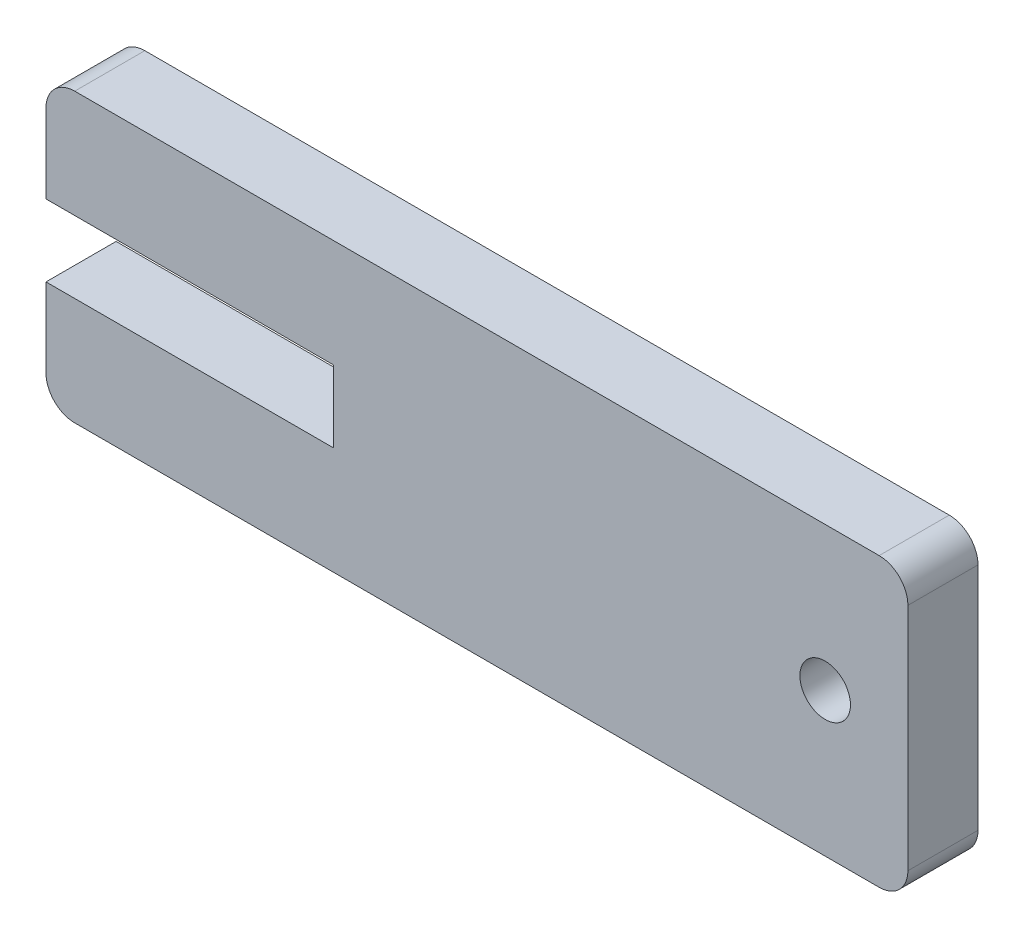
SolidWorks part; units mm, degrees
material "Corrugated Paper"
ref_plane "Front Plane" through (0, 0, 0) normal (0, 0, 1) x (1, 0, 0)
ref_plane "Top Plane" through (0, 0, 0) normal (0, 1, 0) x (1, 0, 0)
ref_plane "Right Plane" through (0, 0, 0) normal (1, 0, 0) x (0, 0, -1)
sketch "Sketch1" plane through (0, 0, 0) normal (0, 0, 1) x (1, 0, 0)
  line L0 (-12.7, 1.5875) -> (-12.7, 6.35)
  line L1 (-12.7, -1.5875) -> (0, -1.5875)
  line L3 (-12.7, 1.5875) -> (0, 1.5875)
  line L4 (0, -1.5875) -> (0, 1.5875)
  line L5 (-12.7, 6.35) -> (25.4, 6.35)
  line L6 (0, 0) -> (25.4, 0) construction
  line L7 (25.4, 6.35) -> (25.4, -6.35)
  line L8 (-12.7, -6.35) -> (25.4, -6.35)
  line L9 (-12.7, -1.5875) -> (-12.7, -6.35)
  dimension "D1" = 12.7
  dimension "D2" = 3.175
  dimension "D3" = 25.4
  dimension "D4" = 12.7
extrude "Boss-Extrude1" add sketch "Sketch1" along normal mid plane 3.0988
fillet "Fillet1" radius 1.27 4 edges at (-12.7, -6.35, 0) (25.4, -6.35, 0) (25.4, 6.35, 0) (-12.7, 6.35, 0)
sketch "Sketch2" plane through (0, 0, 1.5494) normal (0, 0, 1) x (1, 0, 0)
  line L0 (0, 0) -> (25.4, 0) construction
  line L1 (25.4, -5.08) -> (25.4, 5.08) construction
  circle A0 centre (21.7424, 0) radius 1.1176
  dimension "D1" = 2.2352
  dimension "D2" = 2.54
extrude "Cut-Extrude1" cut sketch "Sketch2" against normal through all
equation "\"D2@Sketch1\"=\"thick\"+\"clear\""
equation "\"D1@Sketch2\"=\"rodThick\"+\"clear\""
equation "\"D1@Boss-Extrude1\"= \"thick\""
equation "\"rodThick\"= 0.085in"
equation "\"thick\"= 0.122in"
equation "\"clear\"= 0.003in"
